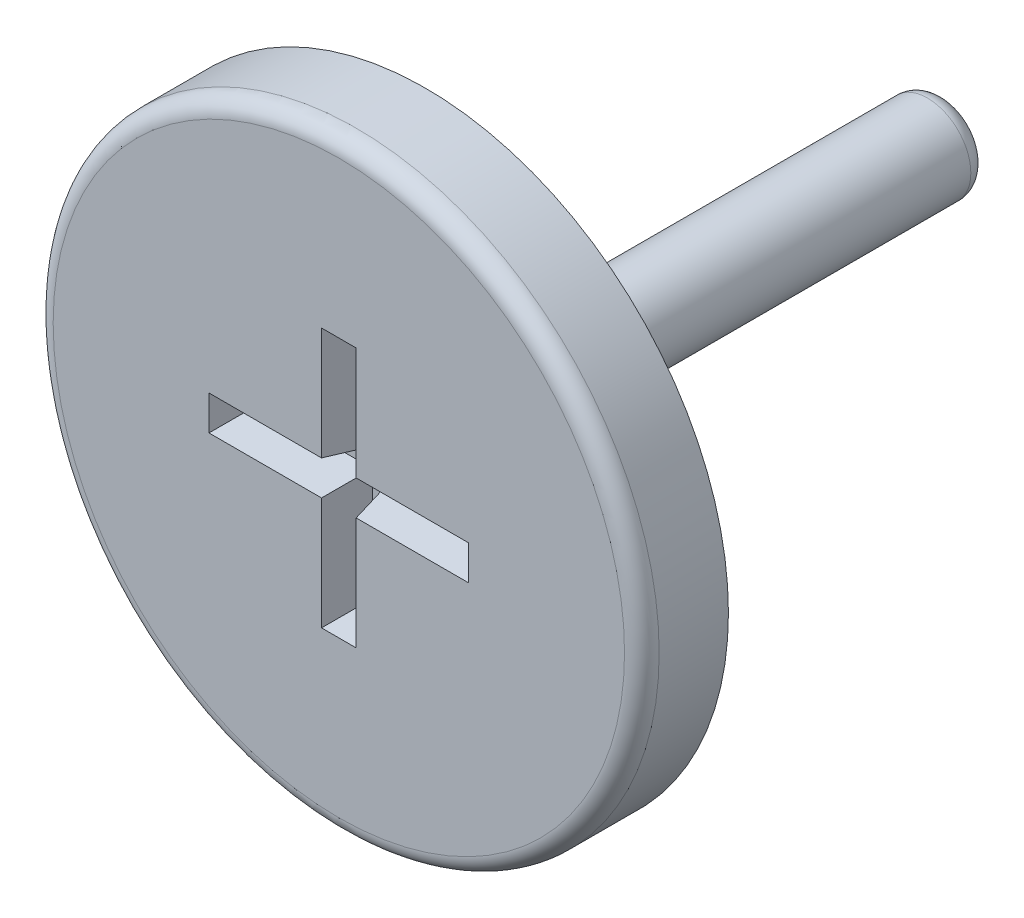
SolidWorks part; units mm, degrees
material "201 Annealed Stainless Steel (SS)"
ref_plane "Front Plane" through (0, 0, 0) normal (0, 0, 1) x (1, 0, 0)
ref_plane "Top Plane" through (0, 0, 0) normal (0, 1, 0) x (1, 0, 0)
ref_plane "Right Plane" through (0, 0, 0) normal (1, 0, 0) x (0, 0, -1)
sketch "Sketch1" plane through (0, 0, 0) normal (0, 0, 1) x (1, 0, 0)
  circle A0 centre (0, 0) radius 3.5
  dimension "D1" = 7
extrude "Boss-Extrude1" add sketch "Sketch1" along normal blind 1
sketch "Sketch2" plane through (0, 0, 0) normal (0, 0, -1) x (-1, 0, 0)
  circle A0 centre (0, 0) radius 0.5
  dimension "D1" = 1
extrude "Boss-Extrude2" add sketch "Sketch2" along normal blind 6
fillet "Fillet1" radius 0.2 1 edges at (3.5, 0, 1)
sketch "Sketch3" plane through (0, 0, 1) normal (0, 0, 1) x (1, 0, 0)
  line L0 (-0.2, -0.2) -> (-0.2, -1.5)
  line L1 (-1.5, -0.2) -> (-0.2, -0.2)
  line L2 (-1.5, -0.2) -> (-1.5, 0.2)
  line L3 (-1.5, 0.2) -> (-0.2, 0.2)
  line L4 (1.5, -0.2) -> (1.5, 0.2)
  line L5 (-0.2, 1.5) -> (0.2, 1.5)
  line L6 (-0.2, 1.5) -> (-0.2, 0.2)
  line L7 (-0.2, -1.5) -> (0.2, -1.5)
  line L8 (0.2, 1.5) -> (0.2, 0.2)
  line L9 (0.2, -0.2) -> (1.5, -0.2)
  line L10 (0.2, -0.2) -> (0.2, -1.5)
  line L11 (0.2, 0.2) -> (1.5, 0.2)
  dimension "D1" = 1.5
  dimension "D2" = 3
  dimension "D3" = 0.2
  dimension "D4" = 0.4
  dimension "D5" = 0.2
  dimension "D6" = 0.4
  dimension "D7" = 1.5
  dimension "D8" = 3
extrude "Cut-Extrude1" cut sketch "Sketch3" against normal blind 0.5 draft 10
fillet "Fillet2" radius 0.2 1 edges at (-0.5, 0, -6)
